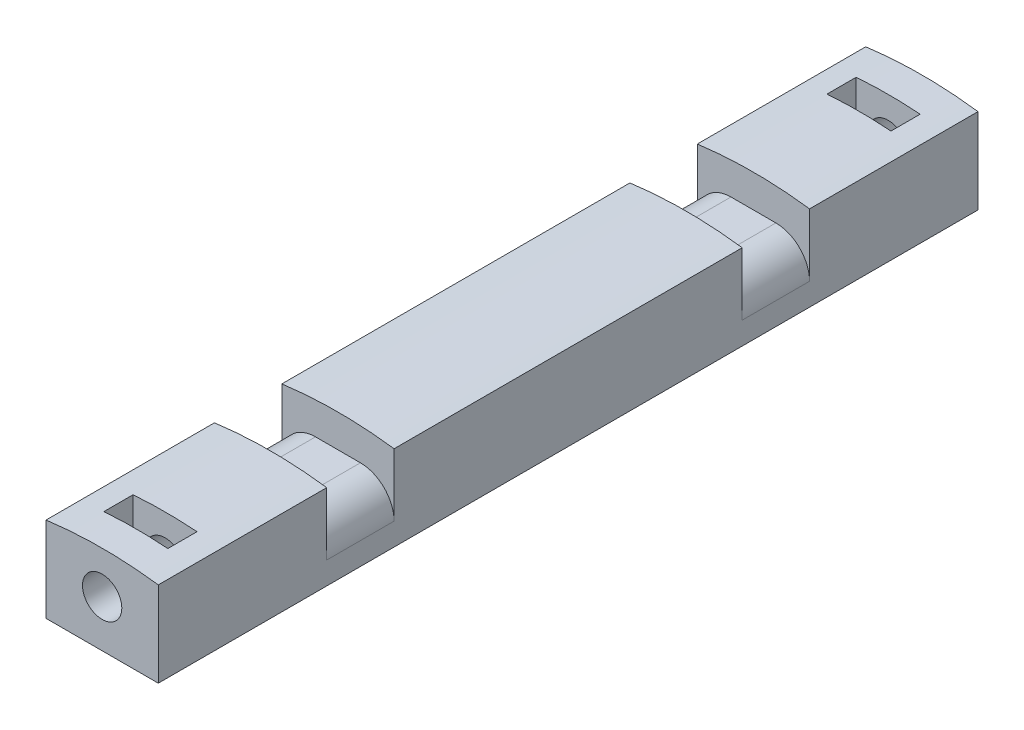
SolidWorks part; units mm, degrees
ref_plane "Plan de face" through (0, 0, 0) normal (0, 0, 1) x (1, 0, 0)
ref_plane "Plan de dessus" through (0, 0, 0) normal (0, 1, 0) x (1, 0, 0)
ref_plane "Plan de droite" through (0, 0, 0) normal (1, 0, 0) x (0, 0, -1)
sketch "Esquisse3" plane through (0, 0, 0) normal (0, 0, 1) x (1, 0, 0)
  line L0 (-5, 29.5804) -> (-5, 37.1652)
  line L1 (5, 29.5804) -> (5, 37.1652)
  line L2 (-5, 29.5804) -> (5, 29.5804)
  line L3 (-5, 37.1652) -> (5, 37.1652) construction
  line L4 (-5, 37.1652) -> (-5, 0) construction
  line L5 (-5, 0) -> (5, 0) construction
  line L6 (5, 37.1652) -> (5, 0) construction
  line L7 (8.9994, 41.4168) -> (9.1038, 41.3823)
  circle A0 centre (0, 0) radius 37.5 construction
  circle A1 centre (0, 0) radius 30 construction
  arc A2 (-5, 37.1652) -> (5, 37.1652) centre (0, 0) cw
  point P5 (0, 0)
  dimension "D1" = 75
  dimension "D2" = 60
  dimension "D3" = 10
extrude "Boss.-Extru.2" add sketch "Esquisse3" along normal blind 73 contours A2 L0 L2 L1
sketch "Esquisse6" plane through (-5, 0, 0) normal (-1, 0, 0) x (0, 0, 1)
  line L0 (73, 29.5804) -> (0, 29.5804) construction
  line L1 (15, 34.5804) -> (21, 34.5804)
  line L2 (15, 34.5804) -> (15, 39.5804)
  line L3 (15, 39.5804) -> (21, 39.5804)
  line L4 (21, 34.5804) -> (21, 39.5804)
  line L5 (52, 34.5804) -> (58, 34.5804)
  line L6 (52, 34.5804) -> (52, 39.5804)
  line L7 (52, 39.5804) -> (58, 39.5804)
  line L8 (58, 34.5804) -> (58, 39.5804)
  line L9 (15, 34.5804) -> (0, 34.5804) construction
  line L10 (0, 29.5804) -> (0, 37.1652) construction
  line L11 (58, 34.5804) -> (73, 34.5804) construction
  line L12 (73, 29.5804) -> (73, 37.1652) construction
  dimension "D1" = 5
  dimension "D2" = 6
  dimension "D3" = 5
  dimension "D4" = 15
extrude "Enlèv. mat.-Extru.3" cut sketch "Esquisse6" against normal through all
sketch "Esquisse7" plane through (0, 0, 73) normal (0, 0, 1) x (1, 0, 0)
  line L0 (-30, 0) -> (-37.5, 0) construction
  circle A0 centre (0, 0) radius 33.75 construction
  circle A1 centre (0, 33.75) radius 1.75
  circle A2 centre (0, 0) radius 37.5 construction
  circle A3 centre (0, 0) radius 30 construction
  arc A4 (5, 37.1652) -> (-5, 37.1652) centre (0, 0) ccw construction
  point P12 (-33.75, 0)
  dimension "D2" = 3.5
  dimension "D3" = 60
extrude "Enlèv. mat.-Extru.4" cut sketch "Esquisse7" against normal blind 12
sketch "Esquisse8" plane through (0, 0, 0) normal (0, 0, -1) x (-1, 0, 0)
  line L0 (-30, 0) -> (-37.5, 0) construction
  circle A0 centre (0, 0) radius 33.75 construction
  circle A1 centre (0, 33.75) radius 1.75
  circle A2 centre (0, 0) radius 37.5 construction
  circle A3 centre (0, 0) radius 30 construction
  arc A4 (5, 37.1652) -> (-5, 37.1652) centre (0, 0) ccw construction
  point P9 (-33.75, 0)
  dimension "D2" = 3.5
  dimension "D3" = 60
extrude "Enlèv. mat.-Extru.5" cut sketch "Esquisse8" against normal blind 12
fillet "Congé1" radius 3 4 edges at (5, 34.5804, 55) (-5, 34.5804, 55) (5, 34.5804, 18) (-5, 34.5804, 18)
sketch "Esquisse9" plane through (0, 0, 0) normal (0, 0, -1) x (-1, 0, 0)
  line L0 (-2.85, 37.3915) -> (-2.85, 31.9954)
  line L1 (-2.85, 31.9954) -> (0, 30.35)
  line L2 (0, 30.35) -> (2.85, 31.9954)
  line L3 (2.85, 31.9954) -> (2.85, 37.3915)
  line L4 (-2.85, 31.9954) -> (2.85, 31.9954) construction
  arc A0 (5, 37.1652) -> (-5, 37.1652) centre (0, 0) ccw construction
  arc A1 (2.85, 37.3915) -> (-2.85, 37.3915) centre (0, 0) ccw
  circle A2 centre (0, 33.75) radius 1.75 construction
  point P9 (0, 31.9954)
  dimension "D3" = 3.4
  dimension "D1" = 120
  dimension "D2" = 5.7
extrude "Enlèv. mat.-Extru.6" cut sketch "Esquisse9" against normal blind 2.6 from offset 3 offset against normal yes
sketch "Esquisse10" plane through (0, 0, 73) normal (0, 0, 1) x (1, 0, 0)
  line L0 (-2.85, 37.3915) -> (-2.85, 31.9954)
  line L1 (-2.85, 31.9954) -> (0, 30.35)
  line L2 (0, 30.35) -> (2.85, 31.9954)
  line L3 (2.85, 31.9954) -> (2.85, 37.3915)
  line L4 (-2.85, 31.9954) -> (2.85, 31.9954) construction
  line L5 (-1.75, 33.75) -> (1.75, 33.75) construction
  line L6 (0, 35.5) -> (0, 32) construction
  circle A0 centre (0, 33.75) radius 1.75 construction
  arc A1 (2.85, 37.3915) -> (-2.85, 37.3915) centre (0, 0) ccw
  circle A2 centre (0, 33.75) radius 1.75 construction
  arc A3 (5, 37.1652) -> (-5, 37.1652) centre (0, 0) ccw construction
  point P9 (0, 31.9954)
  point P19 (0, 33.75)
  dimension "D3" = 3.4
  dimension "D1" = 120
  dimension "D2" = 5.7
extrude "Enlèv. mat.-Extru.7" cut sketch "Esquisse10" against normal blind 2.6 from offset 3
